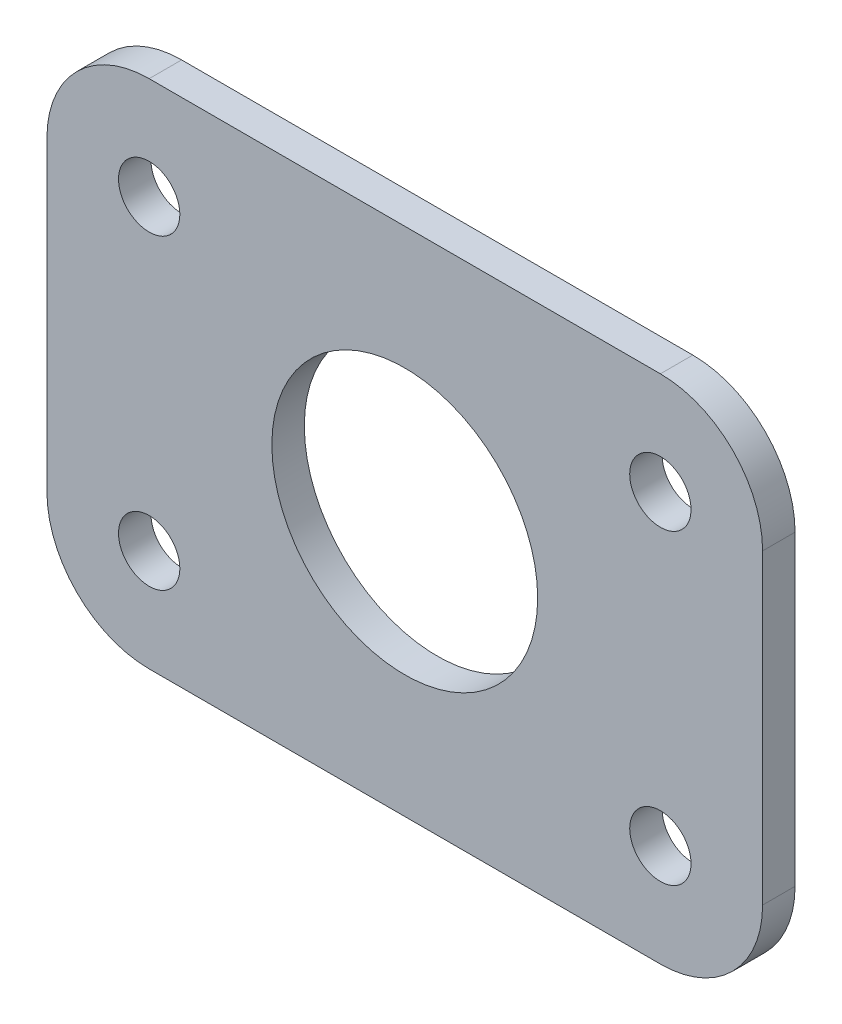
SolidWorks part; units mm, degrees
material "6061 Alloy"
ref_plane "Front Plane" through (0, 0, 0) normal (0, 0, 1) x (1, 0, 0)
ref_plane "Top Plane" through (0, 0, 0) normal (0, 1, 0) x (1, 0, 0)
ref_plane "Right Plane" through (0, 0, 0) normal (1, 0, 0) x (0, 0, -1)
sketch "Sketch1" plane through (0, 0, 0) normal (0, 0, 1) x (1, 0, 0)
  line L0 (0, 0) -> (0, 25)
  line L1 (0, 25) -> (35, 25)
  line L2 (35, 25) -> (35, 0)
  line L6 (0, 0) -> (35, 0)
  line L7 (5, 25) -> (5, 0) construction
  line L8 (0, 0) -> (5, 0) construction
  line L9 (5, 20) -> (5, 25) construction
  line L10 (17.5, 25) -> (17.5, 12.5) construction
  line L15 (17.5, 12.5) -> (17.5, 0) construction
  circle A0 centre (17.5, 12.5) radius 6.5
  circle A1 centre (5, 20) radius 1.5
  circle A2 centre (5, 5) radius 1.5
  circle A5 centre (30, 5) radius 1.5
  circle A6 centre (30, 20) radius 1.5
  circle A8 centre (17.5, 12.5) radius 7.5 construction
  dimension "D5" = 13
  dimension "D7" = 3
  dimension "D4" = 15
  dimension "D1" = 35
  dimension "D2" = 25
  dimension "D3" = 5
  dimension "D6" = 5
  dimension "D8" = 5
extrude "Boss-Extrude1" add sketch "Sketch1" along normal blind 1.5875
fillet "Fillet1" radius 5 4 edges at (0, 25, 0.7937) (35, 25, 0.7937) (35, 0, 0.7937) (0, 0, 0.7937)
